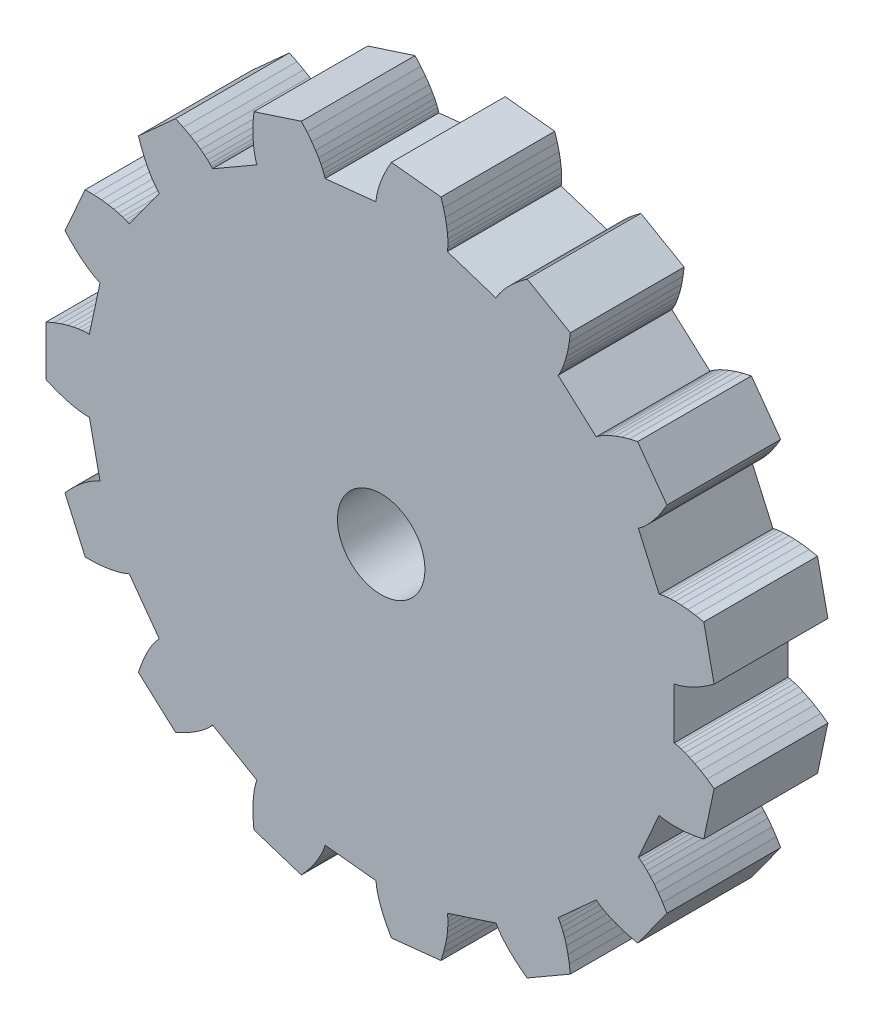
SolidWorks part; units mm, degrees
ref_plane "Front Plane" through (0, 0, 0) normal (0, 0, 1) x (1, 0, 0)
ref_plane "Top Plane" through (0, 0, 0) normal (0, 1, 0) x (1, 0, 0)
ref_plane "Right Plane" through (0, 0, 0) normal (1, 0, 0) x (0, 0, -1)
sketch "Model" plane through (0, 0, 0) normal (0, 0, 1) x (1, 0, 0)
  line L0 (16.7361, -1.4643) -> (16.7361, 1.4643)
  line L1 (16.7361, 1.4643) -> (16.7616, 1.4675)
  line L2 (16.7616, 1.4675) -> (16.8376, 1.4808)
  line L3 (16.8376, 1.4808) -> (16.9628, 1.5098)
  line L4 (16.9628, 1.5098) -> (17.1357, 1.5599)
  line L5 (17.1357, 1.5599) -> (17.354, 1.6365)
  line L6 (17.354, 1.6365) -> (17.6153, 1.7447)
  line L7 (17.6153, 1.7447) -> (17.9167, 1.8893)
  line L8 (17.9167, 1.8893) -> (18.2546, 2.0752)
  line L9 (18.2546, 2.0752) -> (18.6253, 2.3067)
  line L10 (18.6253, 2.3067) -> (19.0248, 2.5879)
  line L11 (15.8847, 5.4694) -> (15.9094, 5.4769)
  line L12 (15.9094, 5.4769) -> (15.9842, 5.4957)
  line L13 (15.9842, 5.4957) -> (16.1104, 5.5201)
  line L14 (16.1104, 5.5201) -> (16.2887, 5.5446)
  line L15 (16.2887, 5.5446) -> (16.5193, 5.5635)
  line L16 (16.5193, 5.5635) -> (16.802, 5.571)
  line L17 (16.802, 5.571) -> (17.1361, 5.5614)
  line L18 (17.1361, 5.5614) -> (17.5204, 5.529)
  line L19 (17.5204, 5.529) -> (17.9533, 5.4684)
  line L20 (17.9533, 5.4684) -> (18.4326, 5.374)
  line L21 (19.0248, 2.5879) -> (18.4326, 5.374)
  line L22 (15.8847, 5.4694) -> (14.6936, 8.1449)
  line L23 (14.6936, 8.1449) -> (14.7156, 8.1582)
  line L24 (14.7156, 8.1582) -> (14.7796, 8.2012)
  line L25 (14.7796, 8.2012) -> (14.8822, 8.2787)
  line L26 (14.8822, 8.2787) -> (15.0197, 8.3948)
  line L27 (15.0197, 8.3948) -> (15.1881, 8.5535)
  line L28 (15.1881, 8.5535) -> (15.3828, 8.7586)
  line L29 (15.3828, 8.7586) -> (15.5992, 9.0133)
  line L30 (15.5992, 9.0133) -> (15.8323, 9.3206)
  line L31 (15.8323, 9.3206) -> (16.0769, 9.6828)
  line L32 (16.0769, 9.6828) -> (16.3274, 10.1022)
  line L33 (12.2868, 11.4575) -> (12.3063, 11.4743)
  line L34 (12.3063, 11.4743) -> (12.367, 11.5219)
  line L35 (12.367, 11.5219) -> (12.4723, 11.5956)
  line L36 (12.4723, 11.5956) -> (12.6252, 11.6905)
  line L37 (12.6252, 11.6905) -> (12.8283, 11.8015)
  line L38 (12.8283, 11.8015) -> (13.0835, 11.9233)
  line L39 (13.0835, 11.9233) -> (13.3926, 12.0505)
  line L40 (13.3926, 12.0505) -> (13.7569, 12.1772)
  line L41 (13.7569, 12.1772) -> (14.177, 12.2979)
  line L42 (14.177, 12.2979) -> (14.6532, 12.4066)
  line L43 (16.3274, 10.1022) -> (14.6532, 12.4066)
  line L44 (12.2868, 11.4575) -> (10.1104, 13.4171)
  line L45 (10.1104, 13.4171) -> (10.1251, 13.4382)
  line L46 (10.1251, 13.4382) -> (10.1661, 13.5036)
  line L47 (10.1661, 13.5036) -> (10.2283, 13.6161)
  line L48 (10.2283, 13.6161) -> (10.3067, 13.7781)
  line L49 (10.3067, 13.7781) -> (10.3959, 13.9916)
  line L50 (10.3959, 13.9916) -> (10.4904, 14.2582)
  line L51 (10.4904, 14.2582) -> (10.5845, 14.5789)
  line L52 (10.5845, 14.5789) -> (10.6725, 14.9544)
  line L53 (10.6725, 14.9544) -> (10.7486, 15.3848)
  line L54 (10.7486, 15.3848) -> (10.8069, 15.8698)
  line L55 (6.5644, 15.4644) -> (6.5753, 15.4877)
  line L56 (6.5753, 15.4877) -> (6.6114, 15.5559)
  line L57 (6.6114, 15.5559) -> (6.6777, 15.666)
  line L58 (6.6777, 15.666) -> (6.7788, 15.8149)
  line L59 (6.7788, 15.8149) -> (6.9191, 15.9989)
  line L60 (6.9191, 15.9989) -> (7.1027, 16.2141)
  line L61 (7.1027, 16.2141) -> (7.3334, 16.4559)
  line L62 (7.3334, 16.4559) -> (7.6146, 16.7199)
  line L63 (7.6146, 16.7199) -> (7.9493, 17.001)
  line L64 (7.9493, 17.001) -> (8.3402, 17.294)
  line L65 (10.8069, 15.8698) -> (8.3402, 17.294)
  line L66 (6.5644, 15.4644) -> (3.7791, 16.3694)
  line L67 (3.7791, 16.3694) -> (3.7839, 16.3947)
  line L68 (3.7839, 16.3947) -> (3.7948, 16.4711)
  line L69 (3.7948, 16.4711) -> (3.8059, 16.5991)
  line L70 (3.8059, 16.5991) -> (3.8116, 16.779)
  line L71 (3.8116, 16.779) -> (3.8063, 17.0104)
  line L72 (3.8063, 17.0104) -> (3.7842, 17.2923)
  line L73 (3.7842, 17.2923) -> (3.7397, 17.6236)
  line L74 (3.7397, 17.6236) -> (3.6674, 18.0024)
  line L75 (3.6674, 18.0024) -> (3.5618, 18.4265)
  line L76 (3.5618, 18.4265) -> (3.4178, 18.8934)
  line L77 (-0.2931, 16.7974) -> (-0.2926, 16.8232)
  line L78 (-0.2926, 16.8232) -> (-0.2873, 16.9001)
  line L79 (-0.2873, 16.9001) -> (-0.2716, 17.0277)
  line L80 (-0.2716, 17.0277) -> (-0.2398, 17.2048)
  line L81 (-0.2398, 17.2048) -> (-0.1865, 17.43)
  line L82 (-0.1865, 17.43) -> (-0.1062, 17.7012)
  line L83 (-0.1062, 17.7012) -> (0.0062, 18.016)
  line L84 (0.0062, 18.016) -> (0.1557, 18.3715)
  line L85 (0.1557, 18.3715) -> (0.3471, 18.7644)
  line L86 (0.3471, 18.7644) -> (0.5851, 19.1911)
  line L87 (3.4178, 18.8934) -> (0.5851, 19.1911)
  line L88 (-0.2931, 16.7974) -> (-3.2057, 16.4913)
  line L89 (-3.2057, 16.4913) -> (-3.2115, 16.5164)
  line L90 (-3.2115, 16.5164) -> (-3.2327, 16.5905)
  line L91 (-3.2327, 16.5905) -> (-3.2746, 16.7121)
  line L92 (-3.2746, 16.7121) -> (-3.3425, 16.8787)
  line L93 (-3.3425, 16.8787) -> (-3.4415, 17.0879)
  line L94 (-3.4415, 17.0879) -> (-3.5764, 17.3365)
  line L95 (-3.5764, 17.3365) -> (-3.7518, 17.621)
  line L96 (-3.7518, 17.621) -> (-3.9719, 17.9377)
  line L97 (-3.9719, 17.9377) -> (-4.2409, 18.2822)
  line L98 (-4.2409, 18.2822) -> (-4.5623, 18.6501)
  line L99 (-7.0999, 15.226) -> (-7.1099, 15.2497)
  line L100 (-7.1099, 15.2497) -> (-7.1364, 15.3222)
  line L101 (-7.1364, 15.3222) -> (-7.1739, 15.4451)
  line L102 (-7.1739, 15.4451) -> (-7.2169, 15.6199)
  line L103 (-7.2169, 15.6199) -> (-7.2598, 15.8473)
  line L104 (-7.2598, 15.8473) -> (-7.2968, 16.1277)
  line L105 (-7.2968, 16.1277) -> (-7.3221, 16.4609)
  line L106 (-7.3221, 16.4609) -> (-7.3301, 16.8465)
  line L107 (-7.3301, 16.8465) -> (-7.315, 17.2833)
  line L108 (-7.315, 17.2833) -> (-7.2712, 17.7699)
  line L109 (-4.5623, 18.6501) -> (-7.2712, 17.7699)
  line L110 (-7.0999, 15.226) -> (-9.6362, 13.7617)
  line L111 (-9.6362, 13.7617) -> (-9.6517, 13.7822)
  line L112 (-9.6517, 13.7822) -> (-9.7012, 13.8413)
  line L113 (-9.7012, 13.8413) -> (-9.7889, 13.9353)
  line L114 (-9.7889, 13.9353) -> (-9.9188, 14.0599)
  line L115 (-9.9188, 14.0599) -> (-10.0943, 14.2108)
  line L116 (-10.0943, 14.2108) -> (-10.3186, 14.383)
  line L117 (-10.3186, 14.383) -> (-10.5945, 14.5716)
  line L118 (-10.5945, 14.5716) -> (-10.9245, 14.7713)
  line L119 (-10.9245, 14.7713) -> (-11.3103, 14.9767)
  line L120 (-11.3103, 14.9767) -> (-11.7536, 15.182)
  line L121 (-12.679, 11.0219) -> (-12.6978, 11.0394)
  line L122 (-12.6978, 11.0394) -> (-12.7515, 11.0949)
  line L123 (-12.7515, 11.0949) -> (-12.8358, 11.1919)
  line L124 (-12.8358, 11.1919) -> (-12.9461, 11.3341)
  line L125 (-12.9461, 11.3341) -> (-13.0778, 11.5244)
  line L126 (-13.0778, 11.5244) -> (-13.2256, 11.7655)
  line L127 (-13.2256, 11.7655) -> (-13.3844, 12.0596)
  line L128 (-13.3844, 12.0596) -> (-13.5485, 12.4086)
  line L129 (-13.5485, 12.4086) -> (-13.7124, 12.8138)
  line L130 (-13.7124, 12.8138) -> (-13.8703, 13.2761)
  line L131 (-11.7536, 15.182) -> (-13.8703, 13.2761)
  line L132 (-12.679, 11.0219) -> (-14.4005, 8.6525)
  line L133 (-14.4005, 8.6525) -> (-14.423, 8.665)
  line L134 (-14.423, 8.665) -> (-14.4923, 8.6989)
  line L135 (-14.4923, 8.6989) -> (-14.6106, 8.749)
  line L136 (-14.6106, 8.749) -> (-14.7799, 8.8101)
  line L137 (-14.7799, 8.8101) -> (-15.0016, 8.8765)
  line L138 (-15.0016, 8.8765) -> (-15.2766, 8.9426)
  line L139 (-15.2766, 8.9426) -> (-15.6054, 9.0026)
  line L140 (-15.6054, 9.0026) -> (-15.988, 9.0509)
  line L141 (-15.988, 9.0509) -> (-16.424, 9.0816)
  line L142 (-16.424, 9.0816) -> (-16.9125, 9.0889)
  line L143 (-16.0659, 4.912) -> (-16.0902, 4.9204)
  line L144 (-16.0902, 4.9204) -> (-16.1617, 4.9492)
  line L145 (-16.1617, 4.9492) -> (-16.2782, 5.0036)
  line L146 (-16.2782, 5.0036) -> (-16.4369, 5.0885)
  line L147 (-16.4369, 5.0885) -> (-16.6345, 5.2088)
  line L148 (-16.6345, 5.2088) -> (-16.8677, 5.369)
  line L149 (-16.8677, 5.369) -> (-17.1323, 5.5731)
  line L150 (-17.1323, 5.5731) -> (-17.4242, 5.8252)
  line L151 (-17.4242, 5.8252) -> (-17.7388, 6.1287)
  line L152 (-17.7388, 6.1287) -> (-18.071, 6.4868)
  line L153 (-16.9125, 9.0889) -> (-18.071, 6.4868)
  line L154 (-16.0659, 4.912) -> (-16.6748, 2.0473)
  line L155 (-16.6748, 2.0473) -> (-16.7004, 2.0495)
  line L156 (-16.7004, 2.0495) -> (-16.7775, 2.0523)
  line L157 (-16.7775, 2.0523) -> (-16.906, 2.05)
  line L158 (-16.906, 2.05) -> (-17.0855, 2.0369)
  line L159 (-17.0855, 2.0369) -> (-17.315, 2.0074)
  line L160 (-17.315, 2.0074) -> (-17.5931, 1.9559)
  line L161 (-17.5931, 1.9559) -> (-17.9179, 1.877)
  line L162 (-17.9179, 1.877) -> (-18.2871, 1.7655)
  line L163 (-18.2871, 1.7655) -> (-18.6979, 1.6162)
  line L164 (-18.6979, 1.6162) -> (-19.1471, 1.4242)
  line L165 (-16.6748, -2.0473) -> (-16.7004, -2.0495)
  line L166 (-16.7004, -2.0495) -> (-16.7775, -2.0523)
  line L167 (-16.7775, -2.0523) -> (-16.906, -2.05)
  line L168 (-16.906, -2.05) -> (-17.0855, -2.0369)
  line L169 (-17.0855, -2.0369) -> (-17.315, -2.0074)
  line L170 (-17.315, -2.0074) -> (-17.5931, -1.9559)
  line L171 (-17.5931, -1.9559) -> (-17.9179, -1.877)
  line L172 (-17.9179, -1.877) -> (-18.2871, -1.7655)
  line L173 (-18.2871, -1.7655) -> (-18.6979, -1.6162)
  line L174 (-18.6979, -1.6162) -> (-19.1471, -1.4242)
  line L175 (-19.1471, 1.4242) -> (-19.1471, -1.4242)
  line L176 (-16.6748, -2.0473) -> (-16.0659, -4.912)
  line L177 (-16.0659, -4.912) -> (-16.0902, -4.9204)
  line L178 (-16.0902, -4.9204) -> (-16.1617, -4.9492)
  line L179 (-16.1617, -4.9492) -> (-16.2782, -5.0036)
  line L180 (-16.2782, -5.0036) -> (-16.4369, -5.0885)
  line L181 (-16.4369, -5.0885) -> (-16.6345, -5.2088)
  line L182 (-16.6345, -5.2088) -> (-16.8677, -5.369)
  line L183 (-16.8677, -5.369) -> (-17.1323, -5.5731)
  line L184 (-17.1323, -5.5731) -> (-17.4242, -5.8252)
  line L185 (-17.4242, -5.8252) -> (-17.7388, -6.1287)
  line L186 (-17.7388, -6.1287) -> (-18.071, -6.4868)
  line L187 (-14.4005, -8.6525) -> (-14.423, -8.665)
  line L188 (-14.423, -8.665) -> (-14.4923, -8.6989)
  line L189 (-14.4923, -8.6989) -> (-14.6106, -8.749)
  line L190 (-14.6106, -8.749) -> (-14.7799, -8.8101)
  line L191 (-14.7799, -8.8101) -> (-15.0016, -8.8765)
  line L192 (-15.0016, -8.8765) -> (-15.2766, -8.9426)
  line L193 (-15.2766, -8.9426) -> (-15.6054, -9.0026)
  line L194 (-15.6054, -9.0026) -> (-15.988, -9.0509)
  line L195 (-15.988, -9.0509) -> (-16.424, -9.0816)
  line L196 (-16.424, -9.0816) -> (-16.9125, -9.0889)
  line L197 (-18.071, -6.4868) -> (-16.9125, -9.0889)
  line L198 (-14.4005, -8.6525) -> (-12.679, -11.0219)
  line L199 (-12.679, -11.0219) -> (-12.6978, -11.0394)
  line L200 (-12.6978, -11.0394) -> (-12.7515, -11.0949)
  line L201 (-12.7515, -11.0949) -> (-12.8358, -11.1919)
  line L202 (-12.8358, -11.1919) -> (-12.9461, -11.3341)
  line L203 (-12.9461, -11.3341) -> (-13.0778, -11.5244)
  line L204 (-13.0778, -11.5244) -> (-13.2256, -11.7655)
  line L205 (-13.2256, -11.7655) -> (-13.3844, -12.0596)
  line L206 (-13.3844, -12.0596) -> (-13.5485, -12.4086)
  line L207 (-13.5485, -12.4086) -> (-13.7124, -12.8138)
  line L208 (-13.7124, -12.8138) -> (-13.8703, -13.2761)
  line L209 (-9.6362, -13.7617) -> (-9.6517, -13.7822)
  line L210 (-9.6517, -13.7822) -> (-9.7012, -13.8413)
  line L211 (-9.7012, -13.8413) -> (-9.7889, -13.9353)
  line L212 (-9.7889, -13.9353) -> (-9.9188, -14.0599)
  line L213 (-9.9188, -14.0599) -> (-10.0943, -14.2108)
  line L214 (-10.0943, -14.2108) -> (-10.3186, -14.383)
  line L215 (-10.3186, -14.383) -> (-10.5945, -14.5716)
  line L216 (-10.5945, -14.5716) -> (-10.9245, -14.7713)
  line L217 (-10.9245, -14.7713) -> (-11.3103, -14.9767)
  line L218 (-11.3103, -14.9767) -> (-11.7536, -15.182)
  line L219 (-13.8703, -13.2761) -> (-11.7536, -15.182)
  line L220 (-9.6362, -13.7617) -> (-7.0999, -15.226)
  line L221 (-7.0999, -15.226) -> (-7.1099, -15.2497)
  line L222 (-7.1099, -15.2497) -> (-7.1364, -15.3222)
  line L223 (-7.1364, -15.3222) -> (-7.1739, -15.4451)
  line L224 (-7.1739, -15.4451) -> (-7.2169, -15.6199)
  line L225 (-7.2169, -15.6199) -> (-7.2598, -15.8473)
  line L226 (-7.2598, -15.8473) -> (-7.2968, -16.1277)
  line L227 (-7.2968, -16.1277) -> (-7.3221, -16.4609)
  line L228 (-7.3221, -16.4609) -> (-7.3301, -16.8465)
  line L229 (-7.3301, -16.8465) -> (-7.315, -17.2833)
  line L230 (-7.315, -17.2833) -> (-7.2712, -17.7699)
  line L231 (-3.2057, -16.4913) -> (-3.2115, -16.5164)
  line L232 (-3.2115, -16.5164) -> (-3.2327, -16.5905)
  line L233 (-3.2327, -16.5905) -> (-3.2746, -16.7121)
  line L234 (-3.2746, -16.7121) -> (-3.3425, -16.8787)
  line L235 (-3.3425, -16.8787) -> (-3.4415, -17.0879)
  line L236 (-3.4415, -17.0879) -> (-3.5764, -17.3365)
  line L237 (-3.5764, -17.3365) -> (-3.7518, -17.621)
  line L238 (-3.7518, -17.621) -> (-3.9719, -17.9377)
  line L239 (-3.9719, -17.9377) -> (-4.2409, -18.2822)
  line L240 (-4.2409, -18.2822) -> (-4.5623, -18.6501)
  line L241 (-7.2712, -17.7699) -> (-4.5623, -18.6501)
  line L242 (-3.2057, -16.4913) -> (-0.2931, -16.7974)
  line L243 (-0.2931, -16.7974) -> (-0.2926, -16.8232)
  line L244 (-0.2926, -16.8232) -> (-0.2873, -16.9001)
  line L245 (-0.2873, -16.9001) -> (-0.2716, -17.0277)
  line L246 (-0.2716, -17.0277) -> (-0.2398, -17.2048)
  line L247 (-0.2398, -17.2048) -> (-0.1865, -17.43)
  line L248 (-0.1865, -17.43) -> (-0.1062, -17.7012)
  line L249 (-0.1062, -17.7012) -> (0.0062, -18.016)
  line L250 (0.0062, -18.016) -> (0.1557, -18.3715)
  line L251 (0.1557, -18.3715) -> (0.3471, -18.7644)
  line L252 (0.3471, -18.7644) -> (0.5851, -19.1911)
  line L253 (3.7791, -16.3694) -> (3.7839, -16.3947)
  line L254 (3.7839, -16.3947) -> (3.7948, -16.4711)
  line L255 (3.7948, -16.4711) -> (3.8059, -16.5991)
  line L256 (3.8059, -16.5991) -> (3.8116, -16.779)
  line L257 (3.8116, -16.779) -> (3.8063, -17.0104)
  line L258 (3.8063, -17.0104) -> (3.7842, -17.2923)
  line L259 (3.7842, -17.2923) -> (3.7397, -17.6236)
  line L260 (3.7397, -17.6236) -> (3.6674, -18.0024)
  line L261 (3.6674, -18.0024) -> (3.5618, -18.4265)
  line L262 (3.5618, -18.4265) -> (3.4178, -18.8934)
  line L263 (0.5851, -19.1911) -> (3.4178, -18.8934)
  line L264 (3.7791, -16.3694) -> (6.5644, -15.4644)
  line L265 (6.5644, -15.4644) -> (6.5753, -15.4877)
  line L266 (6.5753, -15.4877) -> (6.6114, -15.5559)
  line L267 (6.6114, -15.5559) -> (6.6777, -15.666)
  line L268 (6.6777, -15.666) -> (6.7788, -15.8149)
  line L269 (6.7788, -15.8149) -> (6.9191, -15.9989)
  line L270 (6.9191, -15.9989) -> (7.1027, -16.2141)
  line L271 (7.1027, -16.2141) -> (7.3334, -16.4559)
  line L272 (7.3334, -16.4559) -> (7.6146, -16.7199)
  line L273 (7.6146, -16.7199) -> (7.9493, -17.001)
  line L274 (7.9493, -17.001) -> (8.3402, -17.294)
  line L275 (10.1104, -13.4171) -> (10.1251, -13.4382)
  line L276 (10.1251, -13.4382) -> (10.1661, -13.5036)
  line L277 (10.1661, -13.5036) -> (10.2283, -13.6161)
  line L278 (10.2283, -13.6161) -> (10.3067, -13.7781)
  line L279 (10.3067, -13.7781) -> (10.3959, -13.9916)
  line L280 (10.3959, -13.9916) -> (10.4904, -14.2582)
  line L281 (10.4904, -14.2582) -> (10.5845, -14.5789)
  line L282 (10.5845, -14.5789) -> (10.6725, -14.9544)
  line L283 (10.6725, -14.9544) -> (10.7486, -15.3848)
  line L284 (10.7486, -15.3848) -> (10.8069, -15.8698)
  line L285 (8.3402, -17.294) -> (10.8069, -15.8698)
  line L286 (10.1104, -13.4171) -> (12.2868, -11.4575)
  line L287 (12.2868, -11.4575) -> (12.3063, -11.4743)
  line L288 (12.3063, -11.4743) -> (12.367, -11.5219)
  line L289 (12.367, -11.5219) -> (12.4723, -11.5956)
  line L290 (12.4723, -11.5956) -> (12.6252, -11.6905)
  line L291 (12.6252, -11.6905) -> (12.8283, -11.8015)
  line L292 (12.8283, -11.8015) -> (13.0835, -11.9233)
  line L293 (13.0835, -11.9233) -> (13.3926, -12.0505)
  line L294 (13.3926, -12.0505) -> (13.7569, -12.1772)
  line L295 (13.7569, -12.1772) -> (14.177, -12.2979)
  line L296 (14.177, -12.2979) -> (14.6532, -12.4066)
  line L297 (14.6936, -8.1449) -> (14.7156, -8.1582)
  line L298 (14.7156, -8.1582) -> (14.7796, -8.2012)
  line L299 (14.7796, -8.2012) -> (14.8822, -8.2787)
  line L300 (14.8822, -8.2787) -> (15.0197, -8.3948)
  line L301 (15.0197, -8.3948) -> (15.1881, -8.5535)
  line L302 (15.1881, -8.5535) -> (15.3828, -8.7586)
  line L303 (15.3828, -8.7586) -> (15.5992, -9.0133)
  line L304 (15.5992, -9.0133) -> (15.8323, -9.3206)
  line L305 (15.8323, -9.3206) -> (16.0769, -9.6828)
  line L306 (16.0769, -9.6828) -> (16.3274, -10.1022)
  line L307 (14.6532, -12.4066) -> (16.3274, -10.1022)
  line L308 (14.6936, -8.1449) -> (15.8847, -5.4694)
  line L309 (15.8847, -5.4694) -> (15.9094, -5.4769)
  line L310 (15.9094, -5.4769) -> (15.9842, -5.4957)
  line L311 (15.9842, -5.4957) -> (16.1104, -5.5201)
  line L312 (16.1104, -5.5201) -> (16.2887, -5.5446)
  line L313 (16.2887, -5.5446) -> (16.5193, -5.5635)
  line L314 (16.5193, -5.5635) -> (16.802, -5.571)
  line L315 (16.802, -5.571) -> (17.1361, -5.5614)
  line L316 (17.1361, -5.5614) -> (17.5204, -5.529)
  line L317 (17.5204, -5.529) -> (17.9533, -5.4684)
  line L318 (17.9533, -5.4684) -> (18.4326, -5.374)
  line L319 (16.7361, -1.4643) -> (16.7616, -1.4675)
  line L320 (16.7616, -1.4675) -> (16.8376, -1.4808)
  line L321 (16.8376, -1.4808) -> (16.9628, -1.5098)
  line L322 (16.9628, -1.5098) -> (17.1357, -1.5599)
  line L323 (17.1357, -1.5599) -> (17.354, -1.6365)
  line L324 (17.354, -1.6365) -> (17.6153, -1.7447)
  line L325 (17.6153, -1.7447) -> (17.9167, -1.8893)
  line L326 (17.9167, -1.8893) -> (18.2546, -2.0752)
  line L327 (18.2546, -2.0752) -> (18.6253, -2.3067)
  line L328 (18.6253, -2.3067) -> (19.0248, -2.5879)
  line L329 (18.4326, -5.374) -> (19.0248, -2.5879)
extrude "Boss-Extrude1" add sketch "Model" along normal blind 6.5
sketch "Sketch2" plane through (0, 0, 6.5) normal (0, 0, 1) x (1, 0, 0)
  circle A0 centre (0, 0) radius 2.5
  dimension "D1" = 5
extrude "Cut-Extrude1" cut sketch "Sketch2" against normal up to next
